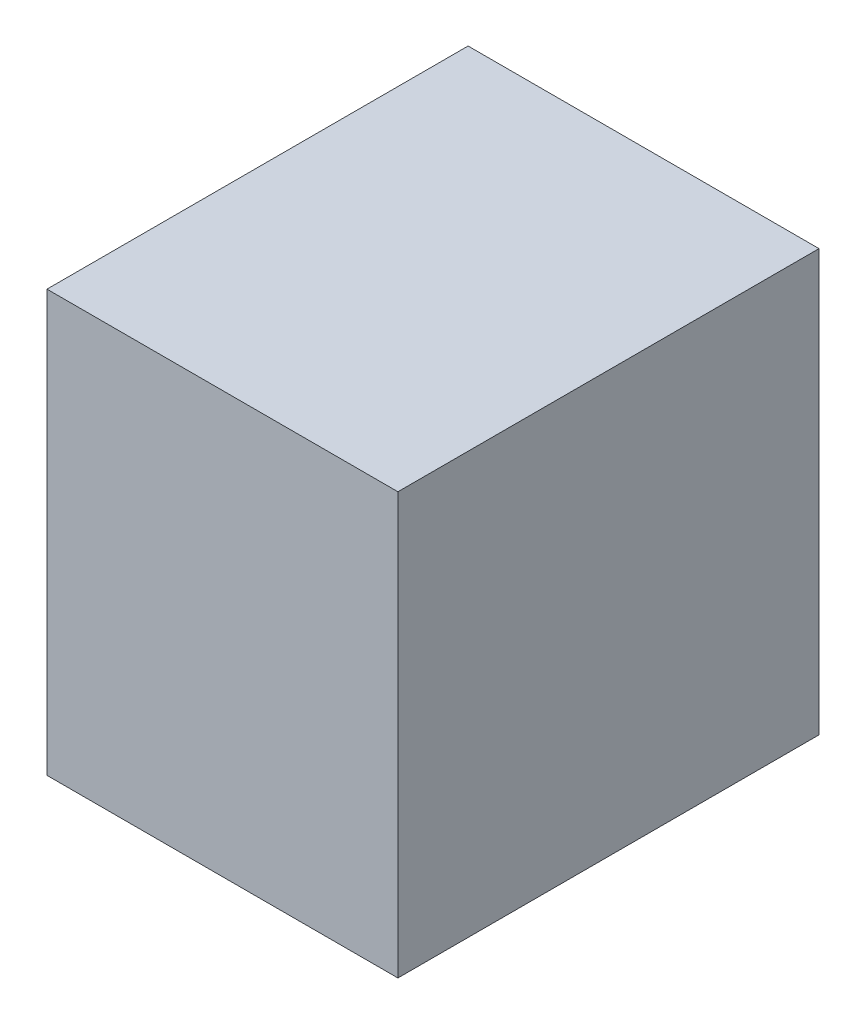
SolidWorks part; units mm, degrees
ref_plane "Front Plane" through (0, 0, 0) normal (0, 0, 1) x (1, 0, 0)
ref_plane "Top Plane" through (0, 0, 0) normal (0, 1, 0) x (1, 0, 0)
ref_plane "Right Plane" through (0, 0, 0) normal (1, 0, 0) x (0, 0, -1)
other "Configuration Table"
sketch "Sketch1" plane through (0, 0, 0) normal (0, 0, 1) x (1, 0, 0)
  line L1 (325, 640) -> (375, 640)
  line L2 (325, 640) -> (325, 700)
  line L3 (325, 700) -> (375, 700)
  line L4 (375, 640) -> (375, 700)
extrude "PACK_flap_servo_25kgcm_2_1" add sketch "Sketch1" against normal blind 60 from offset 170 separate body
